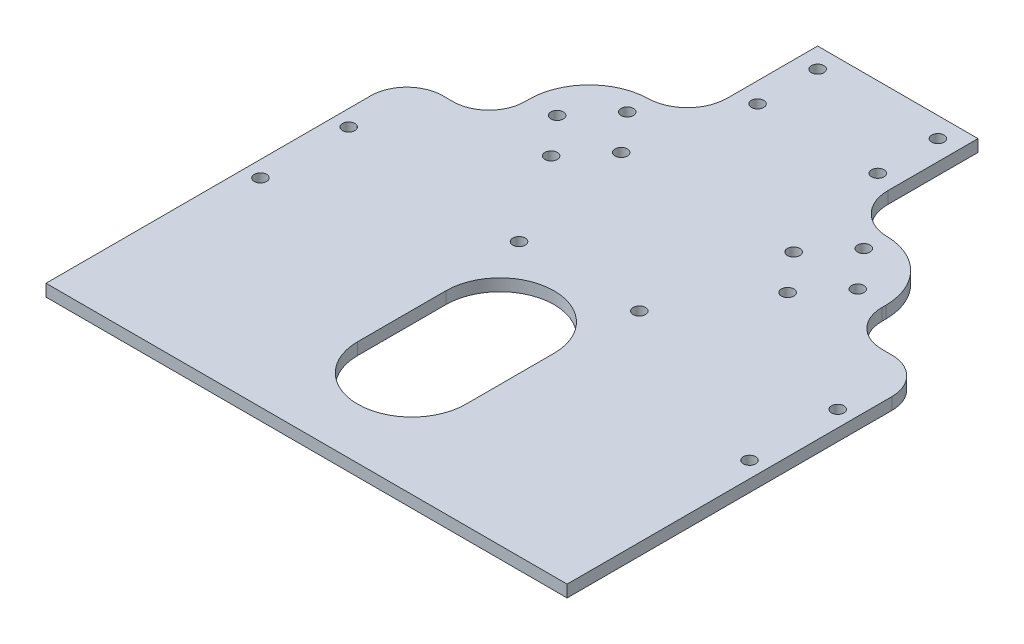
SolidWorks part; units mm, degrees
ref_plane "前视基准面" through (0, 0, 0) normal (0, 0, 1) x (1, 0, 0)
ref_plane "上视基准面" through (0, 0, 0) normal (0, 1, 0) x (1, 0, 0)
ref_plane "右视基准面" through (0, 0, 0) normal (1, 0, 0) x (0, 0, -1)
sketch "草图1" plane through (0, 0, 0) normal (0, 1, 0) x (1, 0, 0)
  line L1 (-100, 100) -> (100, 100)
  line L2 (-100, 100) -> (-100, -100)
  line L3 (-100, -100) -> (100, -100)
  line L4 (100, 100) -> (100, -100)
  line L5 (-100, 100) -> (100, -100) construction
  line L6 (-100, -100) -> (100, 100) construction
  point P0 (0, 0)
  dimension "D1" = 200
  dimension "D2" = 200
extrude "凸台-拉伸1" add sketch "草图1" along normal blind 3
sketch "草图2" plane through (0, 3, 0) normal (0, 1, 0) x (1, 0, 0)
  line L0 (0, 0) -> (0, 91) construction
  line L1 (-100, -100) -> (100, -100) construction
  line L2 (100, 100) -> (-100, 100) construction
  line L3 (-100, 0) -> (100, 0) construction
  line L5 (-100, 100) -> (-100, -100) construction
  line L6 (100, -100) -> (100, 100) construction
  line L7 (-29.5, 0) -> (29.5, 0) construction
  line L8 (-10, 100) -> (10, 100) construction
  line L9 (-10, 100) -> (-10, -100) construction
  line L10 (10, 100) -> (10, -100) construction
  line L11 (0, 0) -> (0, -29) construction
  line L13 (0, -29) -> (0, -32) construction
  circle A0 centre (-29.5, 0) radius 22.5 construction
  circle A1 centre (29.5, 0) radius 22.5 construction
  circle A2 centre (0, -29) radius 10.25 construction
  circle A3 centre (29.5, 0) radius 9.5 construction
  circle A4 centre (29.5, 0) radius 8 construction
  circle A5 centre (-29.5, 0) radius 8 construction
  circle A6 centre (-29.5, 0) radius 9.5 construction
  circle A7 centre (29.5, 9.5) radius 1.55
  circle A8 centre (21.5, 0) radius 1.55
  circle A9 centre (29.5, -9.5) radius 1.55
  circle A10 centre (37.5, 0) radius 1.55
  circle A11 centre (-29.5, -9.5) radius 1.55
  circle A12 centre (-37.5, 0) radius 1.55
  circle A13 centre (-21.5, 0) radius 1.55
  circle A14 centre (-29.5, 9.5) radius 1.55
  circle A15 centre (-15, -32) radius 1.55
  circle A16 centre (15, -32) radius 1.55
  point P16 (0, 0)
  dimension "D1" = 45
  dimension "D3" = 20.5
  dimension "D4" = 19
  dimension "D5" = 16
  dimension "D6" = 3.1
  dimension "D7" = 3.1
  dimension "D8" = 3.1
  dimension "D11" = 3.1
  dimension "D2" = 20
  dimension "D9" = 3
  dimension "D10" = 29
extrude "切除-拉伸2" cut sketch "草图2" against normal blind 10
sketch "草图4" plane through (0, 3, 0) normal (0, 1, 0) x (1, 0, 0)
  line L0 (0, 0) -> (0, 91)
  line L1 (100, 100) -> (-100, 100) construction
  line L2 (-10, 100) -> (10, 100)
  line L3 (-10, 100) -> (-10, -100) construction
  line L4 (-100, -100) -> (100, -100) construction
  line L5 (10, 100) -> (10, -100) construction
  line L6 (21.5, 0) -> (37.5, 0)
  line L7 (-29.5, 0) -> (0, 0)
  line L8 (0, -29) -> (0, 0)
  circle A0 centre (0, -29) radius 10.25
  circle A1 centre (29.5, 0) radius 8 construction
  circle A2 centre (29.5, 0) radius 9.5 construction
  circle A3 centre (29.5, 0) radius 22.5
  circle A4 centre (-29.5, 0) radius 9.5 construction
  circle A5 centre (-29.5, 0) radius 8 construction
  circle A6 centre (-29.5, 0) radius 22.5
  dimension "D1" = 20.5
  dimension "D2" = 19
  dimension "D3" = 16
  dimension "D4" = 45
sketch "草图5" plane through (0, 3, 0) normal (0, 1, 0) x (1, 0, 0)
  line L0 (-65, -100) -> (-189.498, -100)
  line L1 (-44.5, 0) -> (-44.5, -1)
  line L2 (-53.5, -10) -> (-56, -10)
  line L3 (-65, -19) -> (-65, -100)
  line L4 (-20, 47.5) -> (-20, 24.995)
  line L5 (0, 47.5) -> (0, 76.7654)
  line L6 (65, -19) -> (65, -100)
  line L8 (20, 47.5) -> (20, 24.995)
  line L9 (53.5, -10) -> (56, -10)
  line L10 (0, 0) -> (0, 91) construction
  line L11 (0, 47.5) -> (-20, 47.5)
  line L12 (44.5, 0) -> (44.5, -1)
  line L13 (0, 47.5) -> (20, 47.5)
  line L14 (-189.498, -100) -> (-189.498, 163.0721)
  line L15 (-189.498, 163.0721) -> (202.3002, 163.0721)
  line L16 (202.3002, 163.0721) -> (202.3002, -100)
  line L17 (202.3002, -100) -> (65, -100)
  arc A0 (29.8, 14.997) -> (44.5, 0) centre (29.5, 0) cw
  arc A1 (20, 24.995) -> (29.8, 14.997) centre (30, 24.995) ccw
  arc A2 (-29.8, 14.997) -> (-44.5, 0) centre (-29.5, 0) ccw
  arc A3 (-20, 24.995) -> (-29.8, 14.997) centre (-30, 24.995) cw
  circle A4 centre (-29.5, 0) radius 22.5 construction
  arc A5 (-65, -19) -> (-56, -10) centre (-56, -19) cw
  arc A6 (-53.5, -10) -> (-44.5, -1) centre (-53.5, -1) ccw
  arc A7 (65, -19) -> (56, -10) centre (56, -19) ccw
  arc A8 (53.5, -10) -> (44.5, -1) centre (53.5, -1) cw
  dimension "D1" = 10
  dimension "D2" = 15
  dimension "D3" = 45
  dimension "D4" = 9
extrude "切除-拉伸3" cut sketch "草图5" against normal blind 10
sketch "草图6" plane through (0, 0, 0) normal (0, -1, 0) x (1, 0, 0)
  line L0 (20, -47.5) -> (-20, -47.5) construction
  line L7 (-20, -47.5) -> (-20, -24.995) construction
  circle A1 centre (-15, -42.5) radius 1.55
  circle A2 centre (-15, -27.5) radius 1.55
  circle A3 centre (15, -27.5) radius 1.55
  circle A4 centre (15, -42.5) radius 1.55
  dimension "D1" = 3.1
  dimension "D2" = 5
  dimension "D3" = 5
  dimension "D4" = 30
extrude "φ3.1通孔1" cut sketch "草图6" against normal blind 10
sketch "草图7" plane through (0, 3, 0) normal (0, 1, 0) x (1, 0, 0)
  line L0 (0, -29) -> (0, -14.1048) construction
  line L1 (-25.4783, -39.524) -> (-25.4783, -40.524)
  line L3 (-65, -19) -> (-65, -100) construction
  circle A0 centre (-61, -50.5) radius 1.55
  circle A1 centre (-61, -28.5) radius 1.55
  circle A3 centre (61, -50.5) radius 1.55
  circle A4 centre (61, -28.5) radius 1.55
  point P9 (-51, -22.5)
  dimension "D1" = 4
  dimension "D3" = 3.1
  dimension "D4" = 22
  dimension "D5" = 3.1
  dimension "D2" = 10
extrude "φ3.1通孔2" cut sketch "草图7" against normal through all contours A1 | A0 | A4 | A3
sketch "草图9" plane through (0, 3, 0) normal (0, 1, 0) x (1, 0, 0)
  line L2 (-13.5, -51.75) -> (-13.5, -73.75)
  line L3 (13.5, -51.75) -> (13.5, -73.75)
  arc A0 (13.5, -51.75) -> (-13.5, -51.75) centre (0, -51.75) ccw
  arc A1 (-13.5, -73.75) -> (13.5, -73.75) centre (0, -73.75) ccw
  dimension "D1" = 27
extrude "φ21拨单电机孔" cut sketch "草图9" against normal blind 10
